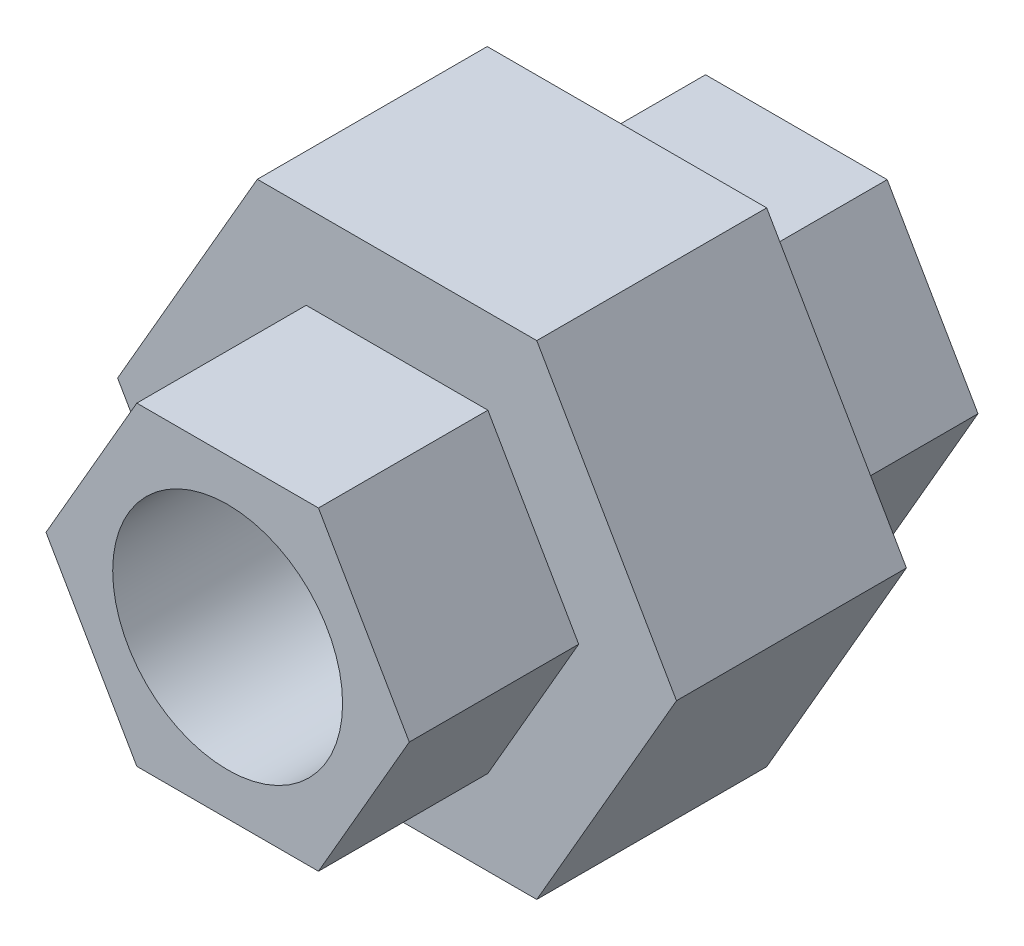
SolidWorks part; units mm, degrees
material "Messing"
ref_plane "Ebene1" through (0, 0, 0) normal (0, 0, 1) x (1, 0, 0)
ref_plane "Ebene2" through (0, 0, 0) normal (0, 1, 0) x (1, 0, 0)
ref_plane "Ebene3" through (0, 0, 0) normal (1, 0, 0) x (0, 0, -1)
sketch "Skizze1" plane through (0, 0, 0) normal (0, 0, 1) x (1, 0, 0)
  line L0 (50, 0) -> (-50, 0) construction
  line L1 (11.547, -20) -> (23.094, 0)
  line L2 (23.094, 0) -> (11.547, 20)
  line L3 (11.547, 20) -> (-11.547, 20)
  line L4 (-11.547, 20) -> (-23.094, 0)
  line L5 (-23.094, 0) -> (-11.547, -20)
  line L6 (-11.547, -20) -> (11.547, -20)
  circle A0 centre (0, 0) radius 20 construction
  dimension "D1" = 40
extrude "Basis-Linear austragen" add sketch "Skizze1" along normal blind 19
sketch "Skizze2" plane through (0, 0, 19) normal (0, 0, 1) x (1, 0, 0)
  line L0 (-11.547, 20) -> (-23.094, 0) construction
  line L1 (7.5056, -13) -> (15.0111, 0)
  line L2 (15.0111, 0) -> (7.5056, 13)
  line L3 (7.5056, 13) -> (-7.5056, 13)
  line L4 (-7.5056, 13) -> (-15.0111, 0)
  line L5 (-15.0111, 0) -> (-7.5056, -13)
  line L6 (-7.5056, -13) -> (7.5056, -13)
  circle A0 centre (0, 0) radius 13 construction
  dimension "D1" = 26
extrude "Aufsatz-Linear austragen1" add sketch "Skizze2" along normal blind 14
sketch "Skizze3" plane through (0, 0, 0) normal (0, 0, -1) x (-1, 0, 0)
  line L0 (-23.094, 0) -> (-11.547, 20) construction
  line L1 (7.5056, -13) -> (15.0111, 0)
  line L2 (15.0111, 0) -> (7.5056, 13)
  line L3 (7.5056, 13) -> (-7.5056, 13)
  line L4 (-7.5056, 13) -> (-15.0111, 0)
  line L5 (-15.0111, 0) -> (-7.5056, -13)
  line L6 (-7.5056, -13) -> (7.5056, -13)
  circle A0 centre (0, 0) radius 13 construction
  dimension "D1" = 26
extrude "Aufsatz-Linear austragen2" add sketch "Skizze3" along normal blind 14
sketch "Skizze4" plane through (0, 0, 33) normal (0, 0, 1) x (1, 0, 0)
  circle A0 centre (0, 0) radius 9.5
  dimension "D1" = 19
extrude "Schnitt-Linear austragen1" cut sketch "Skizze4" against normal through all
cosmetic thread "Gewindedarstellung1" parameters "D1"=16, "D2"=21
cosmetic thread "Gewindedarstellung2" parameters "D1"=16, "D2"=21
